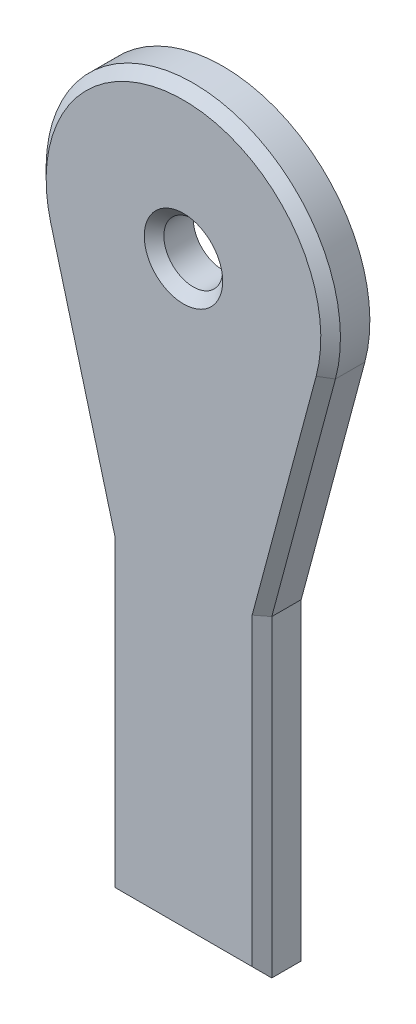
SolidWorks part; units mm, degrees
ref_plane "Front Plane" through (0, 0, 0) normal (0, 0, 1) x (1, 0, 0)
ref_plane "Top Plane" through (0, 0, 0) normal (0, 1, 0) x (1, 0, 0)
ref_plane "Right Plane" through (0, 0, 0) normal (1, 0, 0) x (0, 0, -1)
sketch "Sketch1" plane through (0, 0, 0) normal (0, 0, 1) x (1, 0, 0)
  line L0 (36.2222, -9.7057) -> (20, -70.2479)
  line L1 (20, -70.2479) -> (20, -150)
  line L2 (20, -150) -> (-20, -150)
  line L3 (0, 0) -> (0, -110.6617) construction
  line L4 (-36.2222, -9.7057) -> (-20, -70.2479)
  line L5 (-20, -70.2479) -> (-20, -150)
  arc A0 (36.2222, -9.7057) -> (-36.2222, -9.7057) centre (0, 0) ccw
  circle A1 centre (0, 0) radius 7.5
  point P12 (0, -150)
  dimension "D1" = 75
  dimension "D5" = 15
  dimension "D2" = 150
  dimension "D3" = 20
  dimension "D4" = 15
extrude "Boss-Extrude1" add sketch "Sketch1" along normal blind 10
chamfer "Chamfer1" distance 2.5 angle 45 7 edges at (7.5, 0, 10) (28.1111, -39.9768, 10) (20, -110.1239, 10) (0, -150, 10) (-20, -110.1239, 10) (-28.1111, -39.9768, 10) (0, 37.5, 10)
